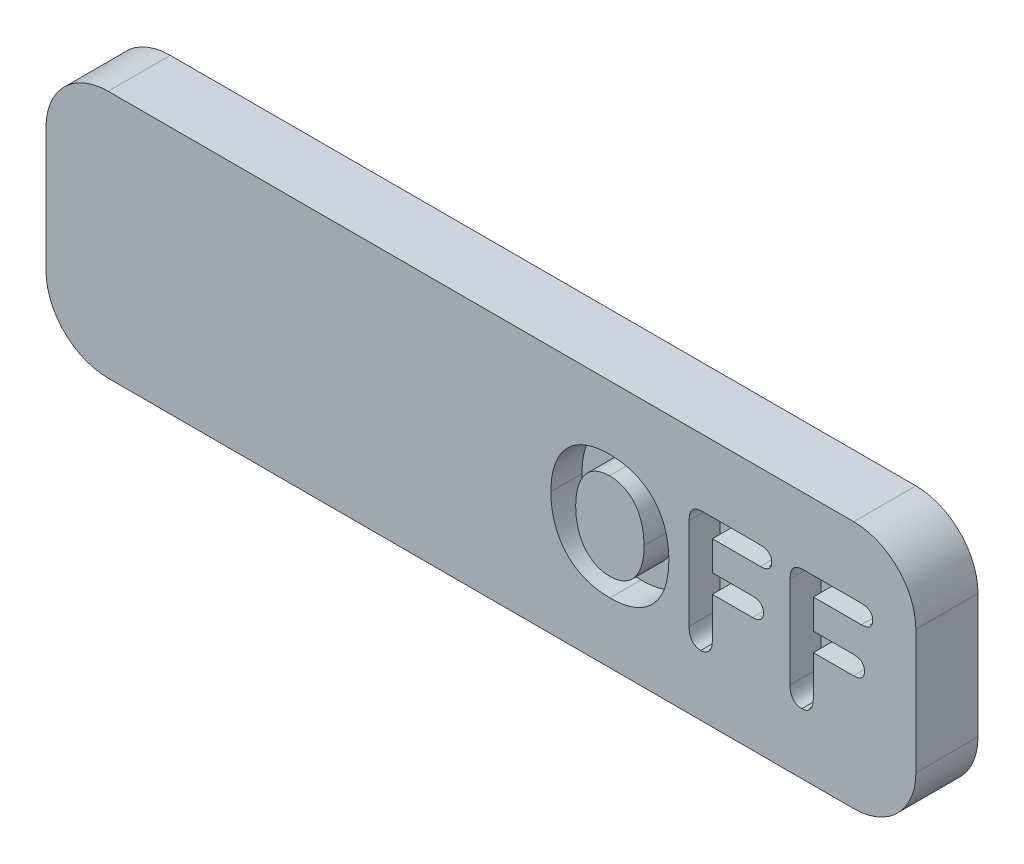
SolidWorks part; units mm, degrees
material "Benutzerdefinierter Kunststoff"
ref_plane "Ebene vorne" through (0, 0, 0) normal (0, 0, 1) x (1, 0, 0)
ref_plane "Ebene oben" through (0, 0, 0) normal (0, 1, 0) x (1, 0, 0)
ref_plane "Ebene rechts" through (0, 0, 0) normal (1, 0, 0) x (0, 0, -1)
sketch "Skizze1" plane through (0, 0, 0) normal (0, 0, 1) x (1, 0, 0)
  line L1 (1, 0) -> (13, 0)
  line L2 (0, 1) -> (0, 3)
  line L3 (1, 4) -> (13, 4)
  line L4 (14, 1) -> (14, 3)
  arc A0 (1, 0) -> (0, 1) centre (1, 1) cw
  arc A1 (0, 3) -> (1, 4) centre (1, 3) cw
  arc A2 (13, 4) -> (14, 3) centre (13, 3) cw
  arc A3 (14, 1) -> (13, 0) centre (13, 1) cw
  point P7 (0, 0)
  point P10 (0, 4)
  point P15 (14, 0)
  dimension "D3" = 1
  dimension "D1" = 14
  dimension "D2" = 4
extrude "Aufsatz-Linear austragen1" add sketch "Skizze1" along normal blind 1
sketch "Skizze2" plane through (0, 0, 1) normal (0, 0, 1) x (1, 0, 0)
  line L0 (1, 0) -> (13, 0) construction
  text T0 "OFF\r\n" font "Arial Rounded MT Bold" height 2
  dimension "D1" = 1
  dimension "D2" = 6
extrude "Schnitt-Linear austragen1" cut sketch "Skizze2" against normal blind 0.5
